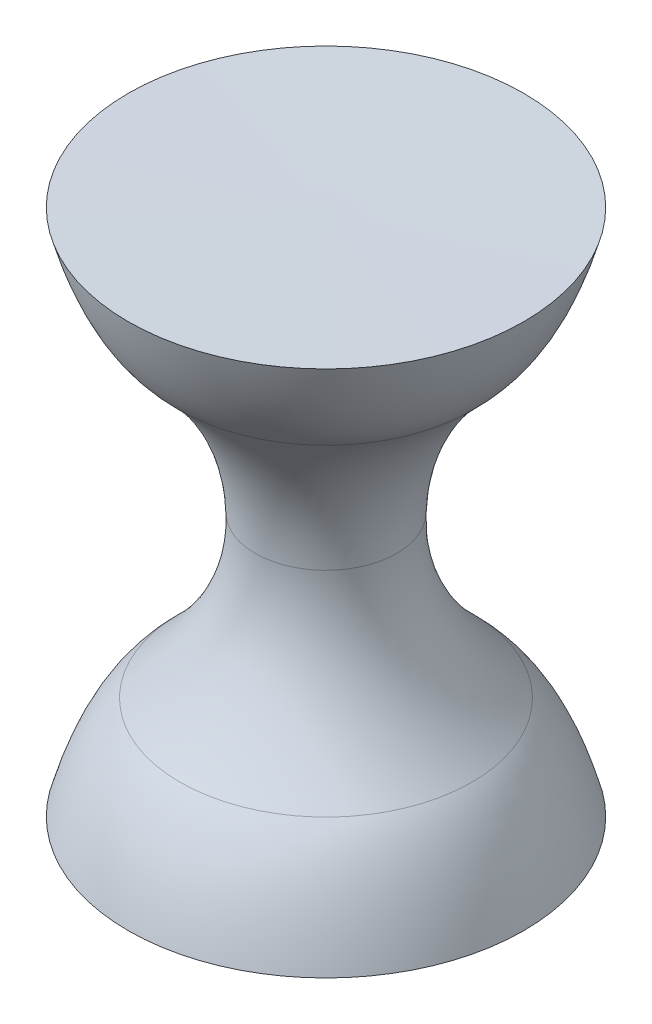
SolidWorks part; units mm, degrees
ref_plane "Front Plane" through (0, 0, 0) normal (0, 0, 1) x (1, 0, 0)
ref_plane "Top Plane" through (0, 0, 0) normal (0, 1, 0) x (1, 0, 0)
ref_plane "Right Plane" through (0, 0, 0) normal (1, 0, 0) x (0, 0, -1)
sketch "Sketch3" plane through (0, 0, 0) normal (0, 0, 1) x (1, 0, 0)
  line L0 (0, 39.8504) -> (0, 0)
  line L1 (0, 0) -> (15, 0)
  line L6 (0, 39.8504) -> (15, 40)
  spline S0 degree 2 poles (15, 0) (13.5017, 5.5076) (11.0751, 7.7912) knots 0 0 0 0.323555 0.323555 0.323555
  spline S1 degree 2 poles (15, 40) (13.5017, 34.4924) (11.0751, 32.2088) knots 0 0 0 0.323555 0.323555 0.323555
  spline S2 degree 3 poles (5.3667, 19.9626) (5.1878, 14.7486) (7.8428, 10.9282) (11.0751, 7.7912) knots 0 0 0 0 0.821474 0.821474 0.821474 0.821474
  spline S3 degree 3 poles (5.3667, 19.9626) (5.4932, 25.1289) (7.8428, 29.0718) (11.0751, 32.2088) knots 0 0 0 0 0.821474 0.821474 0.821474 0.821474
  point P0 (5.3667, 19.9626)
  point P5 (5, 20)
  point P7 (10.8037, 8.0597)
  point P9 (0, 19.9252)
  point P13 (0, 0)
  point P14 (0, 0)
  point P15 (0, 0)
  point P16 (0, 0)
  point P17 (11.0651, 7.8009)
  point P21 (5, 20)
  point P22 (5, 20)
  dimension "D6" = 7.7912
  dimension "D4" = 8.8269
  dimension "D5" = 13.8797
  dimension "D7" = 13.8797
  dimension "D2" = 5.3668
  dimension "D3" = 8.8269
  dimension "D13" = 23.8815
  dimension "D1" = 15
  dimension "D8" = 15
  dimension "D9" = 19.9403
  dimension "D10" = 19.9626
  dimension "D11" = 5.3667
  dimension "D12" = 11.0751
  dimension "D14" = 11.978
revolve "Revolve4" add sketch "Sketch3" angle 360 about L0
